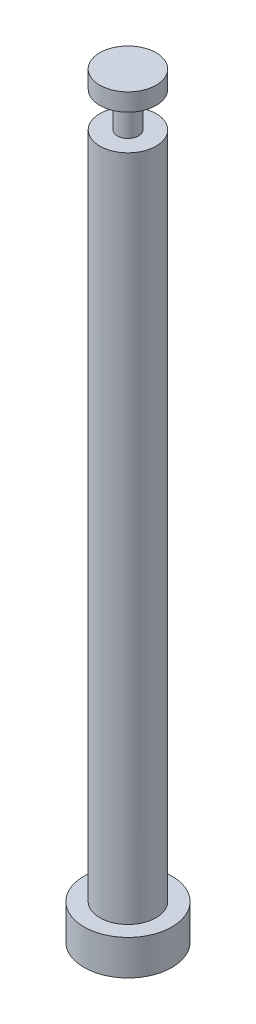
SolidWorks part; units mm, degrees
ref_plane "Front Plane" through (0, 0, 0) normal (0, 0, 1) x (1, 0, 0)
ref_plane "Top Plane" through (0, 0, 0) normal (0, 1, 0) x (1, 0, 0)
ref_plane "Right Plane" through (0, 0, 0) normal (1, 0, 0) x (0, 0, -1)
sketch "Sketch1" plane through (0, 0, 0) normal (0, 1, 0) x (1, 0, 0)
  circle A0 centre (0, 0) radius 1.6
  dimension "D1" = 3.2
extrude "Boss-Extrude1" add sketch "Sketch1" along normal blind 43
sketch "Sketch2" plane through (0, 0, 0) normal (0, 0, 1) x (1, 0, 0)
  line L0 (1.6, 0) -> (1.6, 43) construction
  line L1 (1.6, 42) -> (0.6, 42)
  line L2 (1.6, 42) -> (1.6, 40)
  line L3 (1.6, 40) -> (0.6, 40)
  line L4 (0.6, 42) -> (0.6, 40)
  line L5 (1.6, 43) -> (-1.6, 43) construction
  line L11 (0, 0) -> (0, 10.7223) construction
  dimension "D1" = 1
  dimension "D2" = 2
  dimension "D3" = 1
revolve "Cut-Revolve1" cut sketch "Sketch2" angle 360 about L11
sketch "Sketch3" plane through (0, 0, 0) normal (0, 1, 0) x (1, 0, 0)
  circle A0 centre (0, 0) radius 2.5
  dimension "D1" = 5
extrude "Boss-Extrude2" add sketch "Sketch3" along normal blind 2
